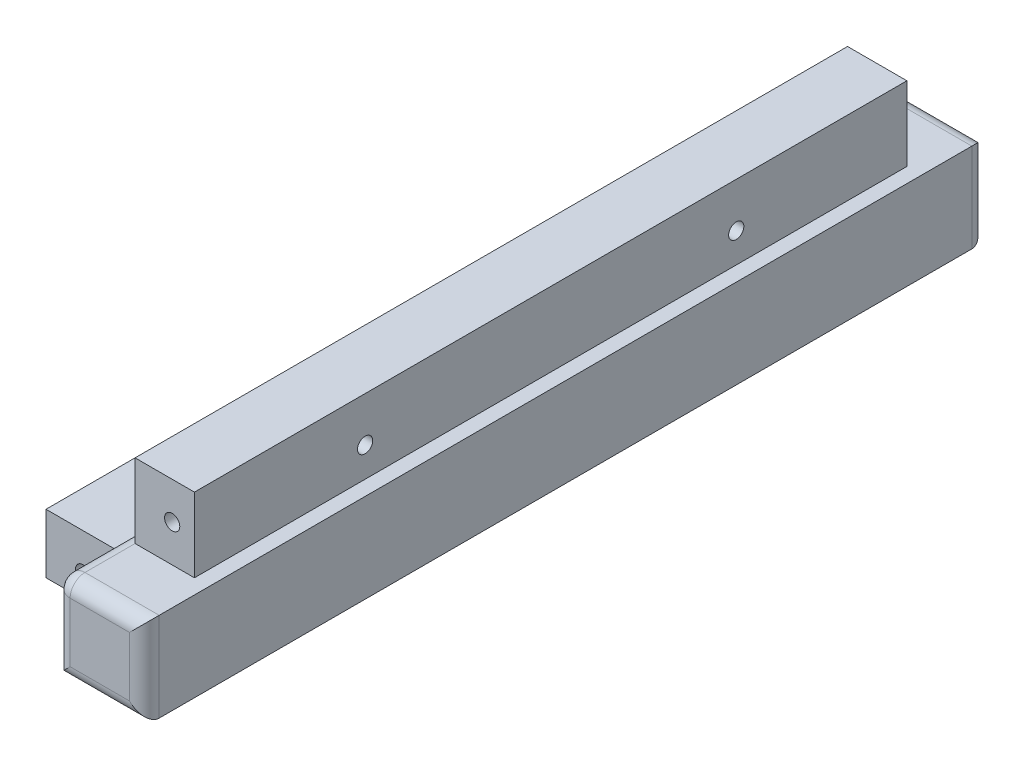
SolidWorks part; units mm, degrees
material "6061-T6 (SS)"
ref_plane "Piano frontale" through (0, 0, 0) normal (0, 0, 1) x (1, 0, 0)
ref_plane "Piano superiore" through (0, 0, 0) normal (0, 1, 0) x (1, 0, 0)
ref_plane "Piano destro" through (0, 0, 0) normal (1, 0, 0) x (0, 0, -1)
sketch "Schizzo1" plane through (0, 0, 0) normal (0, 0, 1) x (1, 0, 0)
  line L1 (-6, 6) -> (6, 6)
  line L2 (-6, 6) -> (-6, -6)
  line L3 (-6, -6) -> (6, -6)
  line L4 (6, 6) -> (6, -6)
  line L5 (-6, 6) -> (6, -6) construction
  line L6 (-6, -6) -> (6, 6) construction
  point P0 (0, 0)
  dimension "D1" = 12
extrude "Estrusione-Estrusione1" add sketch "Schizzo1" along normal mid plane 113.5
fillet "Raccordo1" radius 2 9 edges at (0, 6, -56.75) (-6, 0, -56.75) (0, -6, -56.75) (6, 0, -56.75) (0, -6, 56.75) (-6, 0, 56.75) (0, 6, 56.75) (6, 0, 56.75) (-6, 6, 0)
sketch "Schizzo3" plane through (0, 0, 56.75) normal (0, 0, 1) x (1, 0, 0)
  line L0 (-4, 6) -> (-4, 16)
  line L1 (-4, 6) -> (6, 6) construction
  line L2 (4, 16) -> (4, 6)
  line L3 (4, 6) -> (-4, 6)
  line L4 (-6, -4) -> (-16, -4)
  line L5 (-16, 4) -> (-6, 4)
  line L6 (-6, 4) -> (-6, -4)
  line L7 (0, 0) -> (4, 6) construction
  line L8 (0, 0) -> (-6, 4) construction
  line L9 (-4, 16) -> (4, 16)
  line L10 (-6, -6) -> (-6, 4) construction
  line L11 (6, 6) -> (6, -6) construction
  line L12 (-16, 4) -> (-16, -4)
  point P4 (-16, 0)
  dimension "D1" = 2
  dimension "D2" = 10
  dimension "D4" = 90
  dimension "D5" = 2
  dimension "D3" = 2
extrude "Estrusione-Estrusione3" add sketch "Schizzo3" against normal offset from surface (96 mm away) 8.75 from offset 8.75 up to face at (0, 0, -56.75) offset against normal yes
hole_wizard "Foro filettato M2.5-1" positions "Schizzo4" profile "Schizzo5" tap size "M2.5" standard "ISO"
sketch "Schizzo4" plane through (0, 0, 48) normal (0, 0, 1) x (1, 0, 0)
  line L0 (-4, 6) -> (4, 6) construction
  line L1 (-4, 16) -> (-4, 6) construction
  point P0 (1, 11)
  point P11 (-1.212, 11)
  dimension "D1" = 5
  dimension "D2" = 5
sketch "Schizzo5" plane through (1, 11, 48) normal (1, 0, 0) x (0, -1, 0)
  line L0 (0, 0) -> (0, 7.5)
  line L1 (0, 7.5) -> (1.025, 6.8841)
  line L2 (1.025, 6.8841) -> (1.025, 0)
  line L5 (1.025, 0) -> (0, 0)
  line L10 (0, 7.5) -> (-1.025, 6.8841) construction
  line L11 (0, -6.35) -> (0, 107.95) construction
  dimension "Tap Drill Dia." = 2.05
  dimension "Tap Drill Depth" = 7.5
  dimension "Drill Angle" = 118
cosmetic thread "Filettatura del foro1" parameters "D1"=6, "D2"=2.5
hole_wizard "Foro filettato M2.5-2" positions "Schizzo7" profile "Schizzo8" tap size "M2.5" standard "ISO"
sketch "Schizzo7" plane through (0, 0, 48) normal (0, 0, 1) x (1, 0, 0)
  line L0 (-6, -4) -> (-6, 4) construction
  line L2 (-6, 4) -> (-16, 4) construction
  point P0 (-11, -1)
  dimension "D1" = 5
  dimension "D2" = 5
sketch "Schizzo8" plane through (-11, -1, 48) normal (1, 0, 0) x (0, -1, 0)
  line L0 (0, 0) -> (0, 7.5)
  line L1 (0, 7.5) -> (1.025, 6.8841)
  line L2 (1.025, 6.8841) -> (1.025, 0)
  line L5 (1.025, 0) -> (0, 0)
  line L10 (0, 7.5) -> (-1.025, 6.8841) construction
  line L11 (0, -6.35) -> (0, 107.95) construction
  dimension "Tap Drill Dia." = 2.05
  dimension "Tap Drill Depth" = 7.5
  dimension "Drill Angle" = 118
cosmetic thread "Filettatura del foro2" parameters "D1"=6, "D2"=2.5
mirror "Specchia2" about plane through (0, 0, 0) normal (0, 0, 1) of "Foro filettato M2.5-2", "Foro filettato M2.5-1"
hole_wizard "Foro filettato M2.5-3" positions "Schizzo11" profile "Schizzo12" tap size "M2.5" standard "ISO"
sketch "Schizzo11" plane through (4, 0, 0) normal (1, 0, 0) x (0, 0, -1)
  line L0 (-25, 10) -> (25, 10) construction
  line L3 (48, 6) -> (-48, 6) construction
  point P0 (-25, 10)
  point P2 (25, 10)
  point P9 (0, 10)
  dimension "D1" = 25
  dimension "D2" = 4
sketch "Schizzo12" plane through (4, 10, 25) normal (0, 1, 0) x (0, 0, -1)
  line L0 (0, 0) -> (0, 7.5)
  line L1 (0, 7.5) -> (1.025, 6.8841)
  line L2 (1.025, 6.8841) -> (1.025, 0)
  line L5 (1.025, 0) -> (0, 0)
  line L10 (0, 7.5) -> (-1.025, 6.8841) construction
  line L11 (0, -6.35) -> (0, 107.95) construction
  dimension "Tap Drill Dia." = 2.05
  dimension "Tap Drill Depth" = 7.5
  dimension "Drill Angle" = 118
cosmetic thread "Filettatura del foro3" parameters "D1"=6, "D2"=2.5
cosmetic thread "Filettatura del foro4" parameters "D1"=6, "D2"=2.5
hole_wizard "Foro filettato M2.5-4" positions "Schizzo13" profile "Schizzo14" tap size "M2.5" standard "ISO"
sketch "Schizzo13" plane through (0, -4, 0) normal (0, -1, 0) x (-1, 0, 0)
  line L0 (10, 25) -> (10, -25) construction
  line L2 (6, 48) -> (6, -48) construction
  point P0 (10, 25)
  point P2 (10, -25)
  point P9 (10, 0)
  dimension "D1" = 25
  dimension "D2" = 4
sketch "Schizzo14" plane through (-10, -4, -25) normal (1, 0, 0) x (0, 0, -1)
  line L0 (0, 0) -> (0, 7.5)
  line L1 (0, 7.5) -> (1.025, 6.8841)
  line L2 (1.025, 6.8841) -> (1.025, 0)
  line L5 (1.025, 0) -> (0, 0)
  line L10 (0, 7.5) -> (-1.025, 6.8841) construction
  line L11 (0, -6.35) -> (0, 107.95) construction
  dimension "Tap Drill Dia." = 2.05
  dimension "Tap Drill Depth" = 7.5
  dimension "Drill Angle" = 118
cosmetic thread "Filettatura del foro5" parameters "D1"=6, "D2"=2.5
cosmetic thread "Filettatura del foro6" parameters "D1"=6, "D2"=2.5
